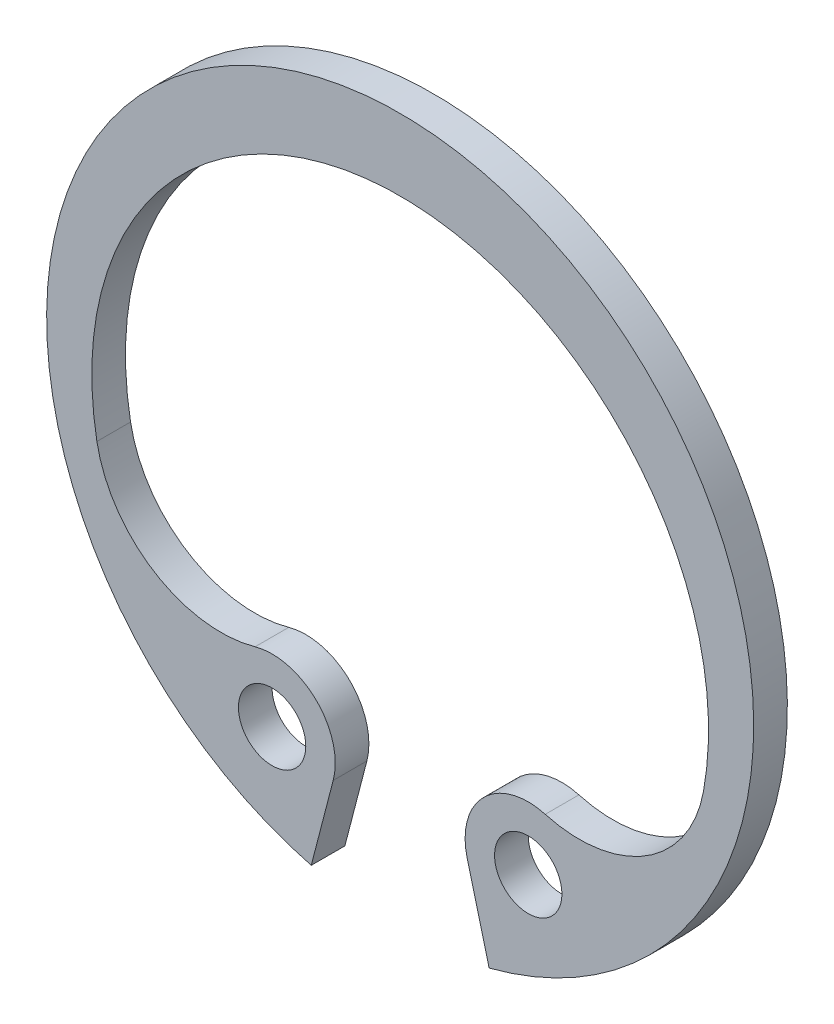
SolidWorks part; units mm, degrees
extrude "Body" add sketch "BodySke" against normal blind 0.4
sketch "BodySke" plane through (0, 0, 0) normal (0, 0, 1) x (1, 0, 0)
  line L0 (-1.5431, 0) -> (1.5431, 0) construction
  line L1 (0, 0) -> (0, 3.35) construction
  line L2 (1.0567, -4.0649) -> (0.7956, -3.0606)
  line L3 (-1.0567, -4.0649) -> (-0.7956, -3.0606)
  line L4 (0, 0) -> (3.9868, -1.3211) construction
  line L5 (0, 0) -> (-3.9868, -1.3211) construction
  line L6 (-1.4208, -2.4847) -> (-1.6221, -3.259) construction
  line L7 (1.3326, -2.1454) -> (1.7103, -3.5983) construction
  arc A0 (-0.7956, -3.0606) -> (-1.7236, -2.1496) centre (-1.5215, -2.8719) ccw
  arc A1 (1.7236, -2.1496) -> (0.7956, -3.0606) centre (1.5215, -2.8719) ccw
  arc A2 (3.5596, -1.1796) -> (-3.5596, -1.1796) centre (0, -0.3135) ccw construction
  arc A3 (1.0567, -4.0649) -> (-1.0567, -4.0649) centre (0, 0) ccw
  circle A4 centre (1.5215, -2.8719) radius 0.4
  circle A5 centre (-1.5215, -2.8719) radius 0.4
  arc A7 (3.603, -0.9766) -> (-3.603, -0.9766) centre (0, -0.3135) ccw
  arc A8 (-1.5215, -2.8719) -> (1.5215, -2.8719) centre (0, 0) ccw construction
  arc A9 (-3.603, -0.9766) -> (-1.7236, -2.1496) centre (-2.1278, -0.7051) ccw
  arc A10 (1.7236, -2.1496) -> (3.603, -0.9766) centre (2.1278, -0.7051) ccw
  dimension "HoleOffsetRad" = 3.25
  dimension "GrooveDia" = 8.4
  dimension "TipRad" = 0.75
  dimension "HoleDia" = 0.8
  dimension "FilletRad" = 1.5
  dimension "LargeRad" = 3.35
  dimension "SmallRad" = 3.75
  dimension "SmallAngle" = 143.332
  dimension "GapAngle" = 29.143
ref_plane "Plane1" through (0, 0, 0) normal (0, 0, 1) x (1, 0, 0)
ref_plane "Plane2" through (0, 0, 0) normal (0, 1, 0) x (1, 0, 0)
ref_plane "Plane3" through (0, 0, 0) normal (1, 0, 0) x (0, 0, -1)
sketch "Clipboard" plane through (0, 0, 0) normal (0, 0, 1) x (1, 0, 0)
  line L0 (0, 0) -> (0.85, 0)
  line L1 (0, 0) -> (0, 0.45)
  line L2 (0, 0) -> (0, -1.7)
  circle A0 centre (0, 0) radius 0.4
  circle A1 centre (0, 0) radius 4
  dimension "HoleDia" = 0.8
  dimension "BoreDia" = 8
  dimension "LargeSection" = 0.85
  dimension "SmallSection" = 0.45
  dimension "LugSection" = 1.7
sketch "ModLugSke" plane through (0, 0, 0) normal (0, 0, 1) x (1, 0, 0)
  line L0 (1.0567, -4.0649) -> (0.7226, -2.7799)
  line L1 (-1.0567, -4.0649) -> (-0.7226, -2.7799)
  line L2 (2.3139, -0.9464) -> (3.8874, -1.59) construction
  line L3 (-2.3139, -0.9464) -> (-3.8874, -1.59) construction
  line L4 (-1.0567, -4.0649) -> (-0.7956, -3.0606) construction
  line L5 (0.7956, -3.0606) -> (1.0567, -4.0649) construction
  line L6 (0, 0) -> (0, -12.7358) construction
  line L7 (3.4844, -1.4251) -> (3.8874, -1.59)
  line L8 (-3.8874, -1.59) -> (-3.4844, -1.4251)
  arc A0 (1.0567, -4.0649) -> (3.8874, -1.59) centre (0, 0) ccw
  arc A1 (-1.3555, -2.1006) -> (-0.9567, -2.3097) centre (0, 0) ccw
  arc A2 (1.0567, -4.0649) -> (-1.0567, -4.0649) centre (0, 0) ccw construction
  arc A3 (1.7236, -2.1496) -> (0.7956, -3.0606) centre (1.5215, -2.8719) ccw construction
  arc A4 (-1.3555, -2.1006) -> (-1.7506, -2.0786) centre (-1.5724, -2.4367) ccw
  arc A5 (-3.4844, -1.4251) -> (-1.7506, -2.0786) centre (-2.3139, -0.9464) ccw
  arc A6 (3.603, -0.9766) -> (-3.603, -0.9766) centre (0, -0.3135) ccw construction
  arc A7 (1.7506, -2.0786) -> (3.4844, -1.4251) centre (2.3139, -0.9464) ccw
  arc A8 (0.9567, -2.3097) -> (1.3555, -2.1006) centre (0, 0) ccw
  arc A9 (-3.8874, -1.59) -> (-1.0567, -4.0649) centre (0, 0) ccw
  circle A10 centre (-1.5215, -2.8719) radius 0.4
  circle A11 centre (-1.5215, -2.8719) radius 0.4 construction
  circle A12 centre (1.5215, -2.8719) radius 0.4
  circle A13 centre (1.5215, -2.8719) radius 0.4 construction
  arc A14 (-0.9567, -2.3097) -> (-0.7226, -2.7799) centre (-1.1098, -2.6793) cw
  arc A15 (0.9567, -2.3097) -> (0.7226, -2.7799) centre (1.1098, -2.6793) ccw
  arc A16 (1.3555, -2.1006) -> (1.7506, -2.0786) centre (1.5724, -2.4367) cw
  point P43 (0.629, -2.4196)
extrude "ModLug" [suppressed] add sketch "ModLugSke" against normal through all
equation "' \"BoreDia@Clipboard\" = 8"
equation "' \"Thickness@Body\" = 0.4"
equation "' \"GrooveDia@BodySke\" = 8.4"
equation "' \"LugSection@Clipboard\" = 1.7"
equation "' \"LargeSection@Clipboard\" = 0.85"
equation "' \"SmallSection@Clipboard\" = 0.45"
equation "' \"HoleDia@Clipboard\" = 0.8"
equation "' \"BoreDia@Clipboard\" = 25"
equation "' \"Thickness@Body\" = 1.1"
equation "' \"GrooveDia@BodySke\" = 26.6"
equation "' \"LugSection@Clipboard\" = 4"
equation "' \"LargeSection@Clipboard\" = 2.6"
equation "' \"SmallSection@Clipboard\" = 1.3"
equation "' \"HoleDia@Clipboard\" = 1.5"
equation "\"TipRad@BodySke\" = (\"LugSection@Clipboard\" - (\"GrooveDia@BodySke\" / 2  -  \"BoreDia@Clipboard\" / 2 ) ) / 2"
equation "\"HoleOffsetRad@BodySke\" = (\"GrooveDia@BodySke\" / 2) - \"LugSection@Clipboard\"  + \"TipRad@BodySke\""
equation "\"LargeRad@BodySke\" =  \"GrooveDia@BodySke\" / 2 -  \"LargeSection@Clipboard\""
equation "\"SmallRad@BodySke\" =  \"GrooveDia@BodySke\" / 2 -  \"SmallSection@Clipboard\""
equation "\"HoleDia@BodySke\" =  \"HoleDia@Clipboard\""
equation "\"FilletRad@BodySke\" = \"TipRad@BodySke\" * 2"
equation "\"GapAngle@BodySke\" = 360 - 0.965 * 360 * ( \"BoreDia@Clipboard\" /  \"GrooveDia@BodySke\")"
equation "\"LugAng@ModLugSke\" = \"GapAngle@BodySke\"  + 1.5 * 360 * (\"LugSection@Clipboard\" / (\"BoreDia@Clipboard\" * 3.1416))"
